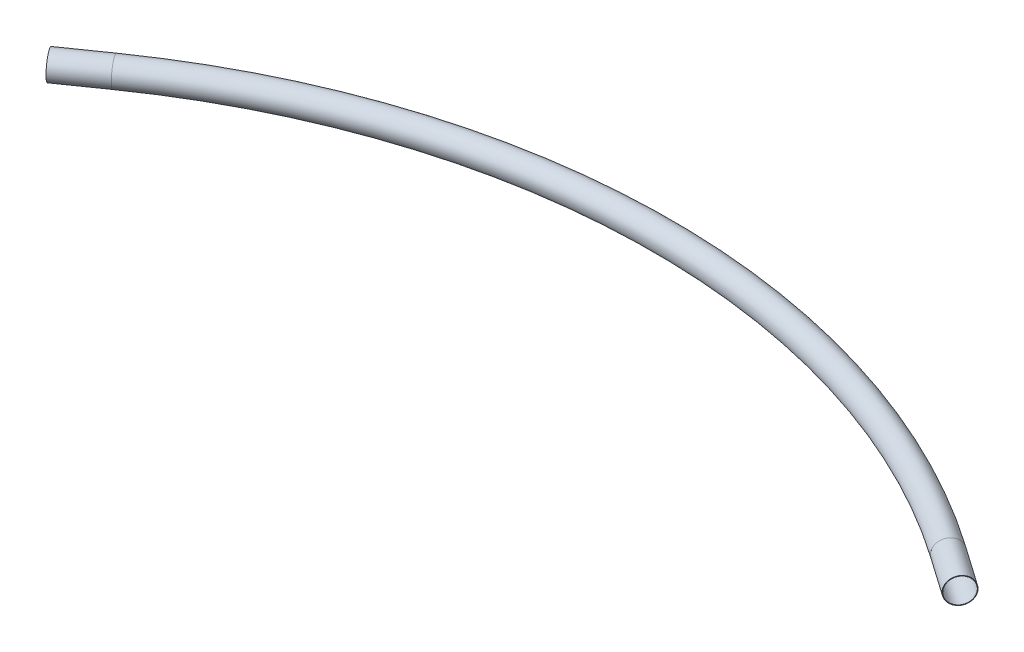
SolidWorks part; units mm, degrees
ref_plane "Front Plane" through (0, 0, 0) normal (0, 0, 1) x (1, 0, 0)
ref_plane "Top Plane" through (0, 0, 0) normal (0, 1, 0) x (1, 0, 0)
ref_plane "Right Plane" through (0, 0, 0) normal (1, 0, 0) x (0, 0, -1)
sketch "Pipe_Definition" plane through (0, 0, 0) normal (0, 1, 0) x (1, 0, 0)
  line L0 (0, 0) -> (0, 854.075) construction
  line L1 (-2711.45, 0) -> (2711.45, 0) construction
  line L6 (-2711.45, 0) -> (-2961.2263, -174.685)
  line L10 (2711.45, 0) -> (2961.2263, -174.685)
  arc A1 (2711.45, 0) -> (-2711.45, 0) centre (0, -3877.0114) ccw
  dimension "D1" = 304.8
  dimension "D3" = 5422.9
  dimension "D4" = 2842.7812
  dimension "D5" = 5922.4525
  dimension "D2" = 854.075
  dimension "D6" = 2711.45
other "Structural Member1"
ref_plane "Plane1" through (2711.45, 0, 0) normal (-0.8195, 0, -0.5731) x (-0.5731, 0, 0.8195)
sketch "Sketch12" plane through (2711.45, 0, 0) normal (-0.8195, 0, -0.5731) x (-0.5731, 0, 0.8195)
  circle A0 centre (0, 0) radius 84.1375
  circle A1 centre (0, 0) radius 80.7339
  point P4 (0, 0)
  dimension "D1" = 168.275
  dimension "D2" = 161.4678
equation "\"D2@Sketch12\" = \"D1@Sketch12\" - .134*2"
